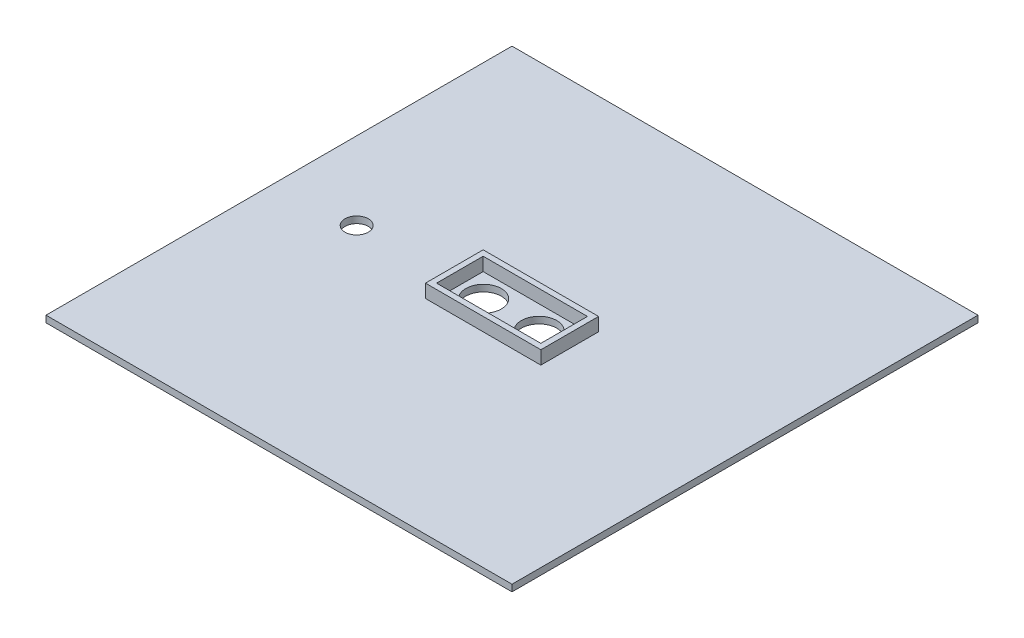
SolidWorks part; units mm, degrees
ref_plane "Front Plane" through (0, 0, 0) normal (0, 0, 1) x (1, 0, 0)
ref_plane "Top Plane" through (0, 0, 0) normal (0, 1, 0) x (1, 0, 0)
ref_plane "Right Plane" through (0, 0, 0) normal (1, 0, 0) x (0, 0, -1)
sketch "Sketch1" plane through (0, 0, 0) normal (0, 1, 0) x (1, 0, 0)
  line L1 (-105, -105) -> (105, -105)
  line L2 (-105, -105) -> (-105, 105)
  line L3 (-105, 105) -> (105, 105)
  line L4 (105, -105) -> (105, 105)
  line L5 (-105, -105) -> (105, 105) construction
  line L6 (-105, 105) -> (105, -105) construction
  point P0 (0, 0)
  dimension "D1" = 210
  dimension "D2" = 210
extrude "Boss-Extrude1" add sketch "Sketch1" along normal blind 3
sketch "Sketch2" plane through (0, 0, 0) normal (0, -1, 0) x (1, 0, 0)
  line L1 (-99.5, -99.5) -> (99.5, -99.5)
  line L2 (-99.5, -99.5) -> (-99.5, 99.5)
  line L3 (-99.5, 99.5) -> (99.5, 99.5)
  line L4 (105, -105) -> (105, 105)
  line L5 (105, 105) -> (-105, 105)
  line L6 (-105, 105) -> (-105, -105)
  line L7 (-105, -105) -> (105, -105)
  line L8 (105, -105) -> (105, 105)
  line L9 (105, 105) -> (-105, 105)
  line L10 (-105, 105) -> (-105, -105)
  line L11 (-105, -105) -> (105, -105)
  line L12 (99.5, -99.5) -> (99.5, 99.5)
  line L13 (-99.5, -99.5) -> (99.5, 99.5) construction
  line L14 (-99.5, 99.5) -> (99.5, -99.5) construction
  line L15 (-96.5, -96.5) -> (96.5, -96.5)
  line L16 (-96.5, -96.5) -> (-96.5, 96.5)
  line L17 (-96.5, 96.5) -> (96.5, 96.5)
  line L18 (96.5, -96.5) -> (96.5, 96.5)
  line L19 (-96.5, -96.5) -> (96.5, 96.5) construction
  line L20 (-96.5, 96.5) -> (96.5, -96.5) construction
  point P2 (0, 0)
  point P10 (0, 0)
  dimension "D2" = 199
  dimension "D3" = 199
  dimension "D4" = 193
  dimension "D5" = 193
  dimension "D1" = 0
extrude "Boss-Extrude2" add sketch "Sketch2" along normal blind 5 contours L1 L12 L3 L2 L18 L15 L16 L17
sketch "Sketch3" plane through (0, 3, 0) normal (0, 1, 0) x (1, 0, 0)
  line L0 (-105, 0) -> (105, 0) construction
  line L1 (-105, 105) -> (-105, -105) construction
  line L2 (105, -105) -> (105, 105) construction
  line L3 (0, 105) -> (0, -105) construction
  line L4 (105, 105) -> (-105, 105) construction
  line L5 (-105, -105) -> (105, -105) construction
  line L7 (-22.5, -10) -> (22.5, -10)
  line L8 (-22.5, -10) -> (-22.5, 10)
  line L9 (-22.5, 10) -> (22.5, 10)
  line L10 (22.5, -10) -> (22.5, 10)
  line L11 (-22.5, -10) -> (22.5, 10) construction
  line L12 (-22.5, 10) -> (22.5, -10) construction
  circle A0 centre (-12.8053, 0) radius 8
  circle A1 centre (12.1947, 0) radius 8
  point P12 (0, 0)
  dimension "D3" = 16
  dimension "D4" = 16
  dimension "D1" = 20
  dimension "D2" = 45
  dimension "D5" = 25
extrude "Cut-Extrude1" cut sketch "Sketch3" against normal through all contours A0 | A1
sketch "Sketch5" plane through (0, 3, 0) normal (0, 1, 0) x (1, 0, 0)
  line L1 (-26, -13) -> (26, -13)
  line L2 (-26, -13) -> (-26, 13)
  line L3 (-26, 13) -> (26, 13)
  line L4 (26, -13) -> (26, 13)
  line L5 (-26, -13) -> (26, 13) construction
  line L6 (-26, 13) -> (26, -13) construction
  line L7 (-23.5, -10.5) -> (23.5, -10.5)
  line L8 (-23.5, -10.5) -> (-23.5, 10.5)
  line L9 (-23.5, 10.5) -> (23.5, 10.5)
  line L10 (23.5, -10.5) -> (23.5, 10.5)
  line L11 (-23.5, -10.5) -> (23.5, 10.5) construction
  line L12 (-23.5, 10.5) -> (23.5, -10.5) construction
  point P0 (0, 0)
  point P6 (0, 0)
  dimension "D1" = 26
  dimension "D2" = 52
  dimension "D3" = 47
  dimension "D4" = 21
extrude "Boss-Extrude4" add sketch "Sketch5" along normal blind 6
sketch "Sketch8" plane through (0, 3, 0) normal (0, 1, 0) x (1, 0, 0)
  line L1 (-5, 15) -> (5, 15)
  line L2 (-5, 15) -> (-5, 19)
  line L3 (-5, 19) -> (5, 19)
  line L4 (5, 15) -> (5, 19)
  line L5 (-5, 15) -> (5, 19) construction
  line L6 (-5, 19) -> (5, 15) construction
  point P0 (0, 17)
  dimension "D1" = 17
  dimension "D2" = 4
  dimension "D3" = 10
extrude "Cut-Extrude2" cut sketch "Sketch8" against normal through all
sketch "Sketch9" plane through (0, 3, 0) normal (0, 1, 0) x (1, 0, 0)
  circle A0 centre (-70, 0) radius 5.25
  dimension "D1" = 10.5
  dimension "D2" = 70
extrude "Cut-Extrude3" cut sketch "Sketch9" against normal through all
